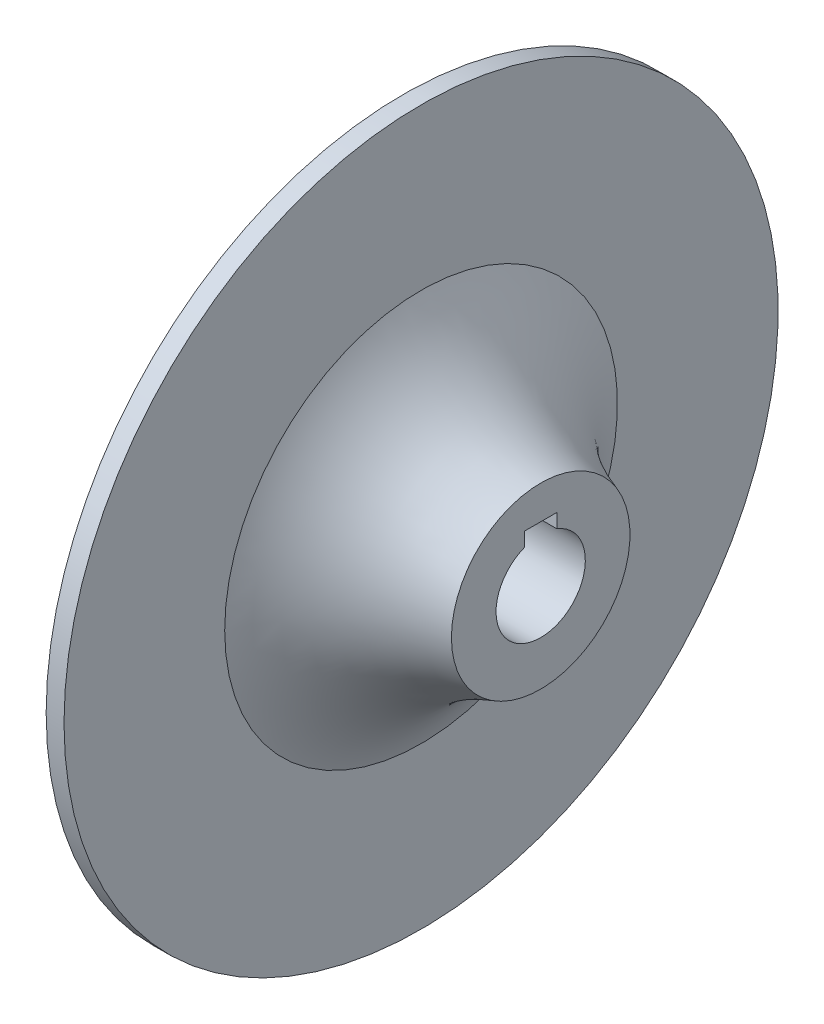
SolidWorks part; units mm, degrees
ref_plane "Front Plane" through (0, 0, 0) normal (0, 0, 1) x (1, 0, 0)
ref_plane "Top Plane" through (0, 0, 0) normal (0, 1, 0) x (1, 0, 0)
ref_plane "Right Plane" through (0, 0, 0) normal (1, 0, 0) x (0, 0, -1)
sketch "Sketch1" plane through (0, 0, 0) normal (0, 0, 1) x (1, 0, 0)
  line L0 (0, 0) -> (0, 12.65)
  line L1 (0, 12.65) -> (-3, 12.65)
  line L2 (-3, 12.65) -> (-3, 27.5)
  line L4 (19.25, 12.5) -> (19.25, 0)
  line L5 (19.25, 0) -> (0, 0)
  line L6 (-3, 27.5) -> (2.5, 27.5)
  line L7 (2.5, 27.5) -> (19.25, 12.5)
  line L8 (-1.2475, 27.5) -> (19.25, 9.1441) construction
  line L9 (0, 27.5) -> (0, 50)
  line L10 (0, 50) -> (2.5, 50)
  line L11 (2.5, 50) -> (2.5, 27.5)
  arc A0 (2.5, 27.5) -> (19.25, 12.5) centre (26.9046, 37.8998) ccw
  dimension "D1" = 27.5
  dimension "D2" = 19.25
  dimension "D3" = 12.5
  dimension "D4" = 2.5
  dimension "D5" = 3
  dimension "D6" = 50
  dimension "D7" = 12.65
  dimension "D8" = 2.5
sketch "Sketch2" plane through (0, 0, 0) normal (0, 0, 1) x (1, 0, 0)
  line L0 (-75.1177, 0) -> (107.7478, 0) construction
revolve "Revolve1" add sketch "Sketch1" angle 360 about L0
sketch "Sketch3" plane through (0, 0, 0) normal (-1, 0, 0) x (0, 0, 1)
  line L1 (-2.4, 0) -> (2.4, 0)
  line L2 (-2.4, 0) -> (-2.4, 8.8)
  line L3 (-2.4, 8.8) -> (2.4, 8.8)
  line L4 (2.4, 0) -> (2.4, 8.8)
  circle A0 centre (0, 0) radius 6.9
  dimension "D1" = 13.8
  dimension "D2" = 8.8
  dimension "D3" = 4.8
extrude "Boss-Extrude1" add sketch "Sketch3" along normal blind 14 contours A0 L4 L3 L2 | L4 A0 L2 L1 | L2 A0 L4 L1
sketch "Sketch5" plane through (19.25, 0, 0) normal (1, 0, 0) x (0, 0, -1)
  line L1 (-2.25, 7.8) -> (2.25, 7.8)
  line L2 (-2.25, 7.8) -> (-2.25, 0)
  line L3 (-2.25, 0) -> (2.25, 0)
  line L4 (2.25, 7.8) -> (2.25, 0)
  circle A0 centre (0, 0) radius 6.25
  dimension "D1" = 12.5
  dimension "D2" = 4.5
  dimension "D3" = 7.8
extrude "Cut-Extrude2" cut sketch "Sketch5" against normal blind 23.25 contours A0 L4 L1 L2 | L4 A0 L2 L3 | L2 A0 L4 L3
sketch "Sketch6" plane through (-4, 0, 0) normal (1, 0, 0) x (0, 0, -1)
  circle A0 centre (0, 0) radius 2.25
  dimension "D1" = 4.5
extrude "Cut-Extrude3" cut sketch "Sketch6" against normal through all
sketch "Sketch7" plane through (0, 0, 0) normal (-1, 0, 0) x (0, 0, 1)
  circle A0 centre (0, 0) radius 50
  circle A1 centre (0, 0) radius 50 construction
  circle A2 centre (0, 0) radius 12.65
  circle A3 centre (0, 0) radius 12.65 construction
extrude "Cut-Extrude6" cut sketch "Sketch7" along normal through all
